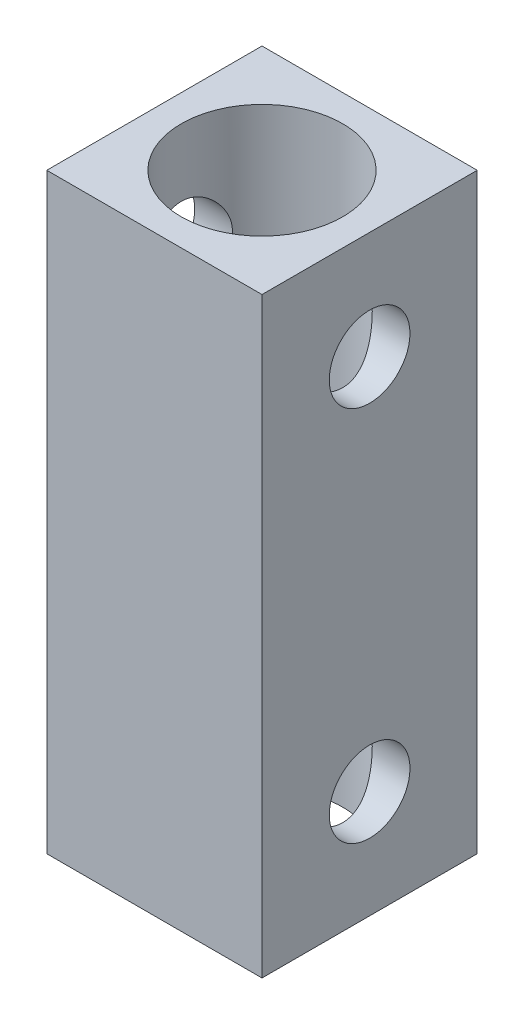
SolidWorks part; units mm, degrees
ref_plane "Front Plane" through (0, 0, 0) normal (0, 0, 1) x (1, 0, 0)
ref_plane "Top Plane" through (0, 0, 0) normal (0, 1, 0) x (1, 0, 0)
ref_plane "Right Plane" through (0, 0, 0) normal (1, 0, 0) x (0, 0, -1)
sketch "Sketch1" plane through (0, 0, 0) normal (0, 1, 0) x (1, 0, 0)
  line L1 (-4, -4) -> (4, -4)
  line L2 (-4, -4) -> (-4, 4)
  line L3 (-4, 4) -> (4, 4)
  line L4 (4, -4) -> (4, 4)
  line L5 (-4, -4) -> (4, 4) construction
  line L6 (-4, 4) -> (4, -4) construction
  circle A0 centre (0, 0) radius 3
  point P0 (0, 0)
  dimension "D1" = 6
  dimension "D2" = 4
extrude "Boss-Extrude2" add sketch "Sketch1" along normal blind 22
sketch "Sketch2" plane through (4, 0, 0) normal (1, 0, 0) x (0, 0, -1)
  line L0 (-4, 0) -> (4, 0) construction
  line L2 (-4, 22) -> (4, 22) construction
  line L3 (4, 11) -> (-4, 11) construction
  line L4 (4, 22) -> (4, 0) construction
  line L5 (-4, 22) -> (-4, 0) construction
  circle A0 centre (0, 18) radius 1.5
  circle A1 centre (0, 4) radius 1.5
  point P6 (0, 0)
  dimension "D1" = 3
  dimension "D2" = 4
extrude "Cut-Extrude1" cut sketch "Sketch2" against normal up to surface (8 mm away) up to face at (-4, 11, 0)
